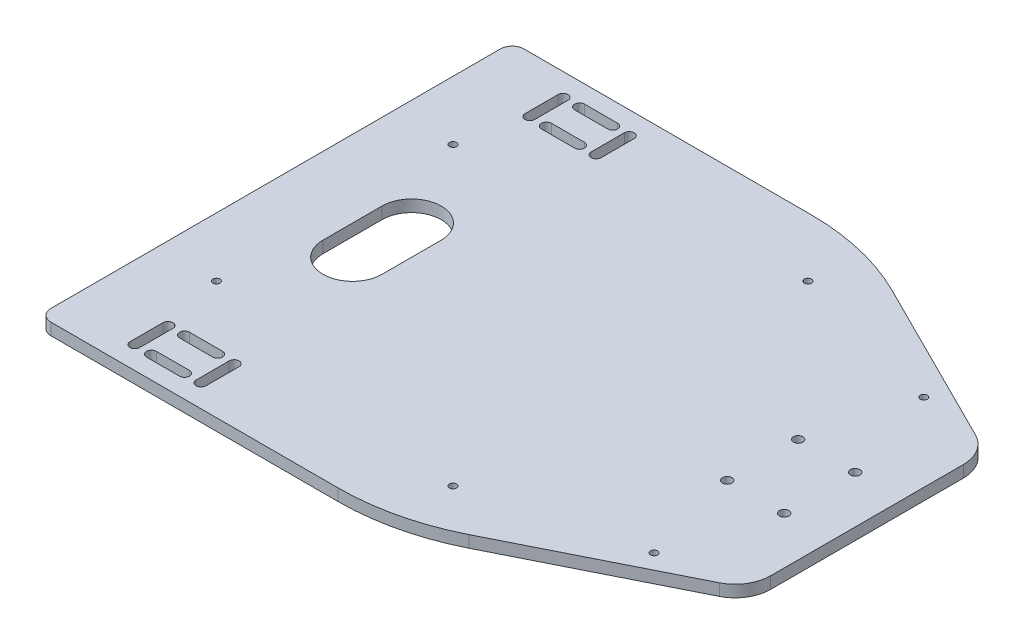
SolidWorks part; units mm, degrees
other "Markup1"
sketch "Sketch6" plane through (-125, 0, -100) normal (0, 1, 0) x (1, 0, 0)
other "Markup2"
sketch "Sketch13" plane through (-125, 0, -100) normal (0, 1, 0) x (1, 0, 0)
other "DetailItem1"
other "DetailItem2"
other "DetailItem4"
other "DetailItem5"
other "DetailItem6"
other "DetailItem7"
material "Acrylic (Medium-high impact)"
ref_plane "Front Plane" through (0, 0, 0) normal (0, 0, 1) x (1, 0, 0)
ref_plane "Top Plane" through (0, 0, 0) normal (0, 1, 0) x (1, 0, 0)
ref_plane "Right Plane" through (0, 0, 0) normal (1, 0, 0) x (0, 0, -1)
sketch "Sketch1" plane through (0, 0, 0) normal (0, 1, 0) x (1, 0, 0)
  line L1 (-120, 100) -> (1.3932, 100)
  line L2 (-125, 95) -> (-125, -95)
  line L3 (-120, -100) -> (1.3932, -100)
  line L4 (125, 40.7295) -> (125, -40.7295)
  line L5 (-125, 100) -> (125, -100) construction
  line L6 (-125, -100) -> (125, 100) construction
  line L7 (46.1146, 89.4427) -> (116.7082, 54.1459)
  line L8 (46.1146, -89.4427) -> (116.7082, -54.1459)
  arc A0 (1.3932, -100) -> (46.1146, -89.4427) centre (1.3932, 0) ccw
  arc A1 (1.3932, 100) -> (46.1146, 89.4427) centre (1.3932, 0) cw
  arc A2 (116.7082, -54.1459) -> (125, -40.7295) centre (110, -40.7295) ccw
  arc A3 (116.7082, 54.1459) -> (125, 40.7295) centre (110, 40.7295) cw
  arc A4 (-125, -95) -> (-120, -100) centre (-120, -95) ccw
  arc A5 (-120, 100) -> (-125, 95) centre (-120, 95) ccw
  point P0 (0, 0)
  point P12 (25, -100)
  point P15 (25, 100)
  point P18 (125, -50)
  point P21 (125, 50)
  dimension "D7" = 100
  dimension "D8" = 15
  dimension "D9" = 5
  dimension "D1" = 200
  dimension "D2" = 250
  dimension "D3" = 100
  dimension "D4" = 100
  dimension "D5" = 50
  dimension "D6" = 100
extrude "Boss-Extrude2" add sketch "Sketch1" against normal blind 5
sketch "Sketch7" plane through (0, 0, 0) normal (0, 1, 0) x (1, 0, 0)
  line L0 (-100, 50.0036) -> (-100, -50.0036) construction
  line L1 (-125, 95) -> (-125, -95) construction
  circle A0 centre (-100, 50.0036) radius 1.5
  circle A1 centre (-100, -49.9964) radius 1.5
  circle A2 centre (25, 75.0036) radius 1.5
  circle A4 centre (25, -74.9964) radius 1.5
  point P9 (-100, 0)
  dimension "D1" = 100
  dimension "D5" = 125
  dimension "D4" = 25
  dimension "D2" = 125
  dimension "D3" = 25
  dimension "D6" = 25
extrude "Cut-Extrude1" cut sketch "Sketch7" against normal blind 5
sketch "Sketch8" plane through (0, 0, 0) normal (0, 1, 0) x (1, 0, 0)
  line L0 (1.3932, 100) -> (-120, 100) construction
  line L1 (-100, 100) -> (-60, 100) construction
  line L2 (-100, 100) -> (-100, 70) construction
  line L3 (-100, 70) -> (-60, 70) construction
  line L4 (-60, 100) -> (-60, 70) construction
  line L5 (-125, 95) -> (-125, -95) construction
  line L8 (-96.1, 90.5) -> (-96.1, 76.5)
  line L10 (-91.9, 90.5) -> (-91.9, 76.5)
  line L11 (-68.1, 90.5) -> (-68.1, 76.5)
  line L13 (-63.9, 90.5) -> (-63.9, 76.5)
  line L14 (-87, 88.4) -> (-73, 88.4)
  line L16 (-87, 92.6) -> (-73, 92.6)
  line L18 (-87, 74.4) -> (-73, 74.4)
  line L20 (-87, 78.6) -> (-73, 78.6)
  line L21 (-125, 0) -> (47.5239, 0) construction
  line L23 (-87, -78.6) -> (-73, -78.6)
  line L24 (-87, -74.4) -> (-73, -74.4)
  line L25 (-87, -92.6) -> (-73, -92.6)
  line L26 (-87, -88.4) -> (-73, -88.4)
  line L27 (-63.9, -90.5) -> (-63.9, -76.5)
  line L28 (-68.1, -90.5) -> (-68.1, -76.5)
  line L29 (-91.9, -90.5) -> (-91.9, -76.5)
  line L30 (-96.1, -90.5) -> (-96.1, -76.5)
  arc A0 (-91.9, 90.5) -> (-96.1, 90.5) centre (-94, 90.5) ccw
  arc A1 (-96.1, 76.5) -> (-91.9, 76.5) centre (-94, 76.5) ccw
  arc A2 (-63.9, 90.5) -> (-68.1, 90.5) centre (-66, 90.5) ccw
  arc A3 (-68.1, 76.5) -> (-63.9, 76.5) centre (-66, 76.5) ccw
  arc A4 (-87, 92.6) -> (-87, 88.4) centre (-87, 90.5) ccw
  arc A5 (-73, 88.4) -> (-73, 92.6) centre (-73, 90.5) ccw
  arc A6 (-87, 78.6) -> (-87, 74.4) centre (-87, 76.5) ccw
  arc A7 (-73, 74.4) -> (-73, 78.6) centre (-73, 76.5) ccw
  arc A8 (-73, -74.4) -> (-73, -78.6) centre (-73, -76.5) cw
  arc A9 (-87, -78.6) -> (-87, -74.4) centre (-87, -76.5) cw
  arc A10 (-73, -88.4) -> (-73, -92.6) centre (-73, -90.5) cw
  arc A11 (-87, -92.6) -> (-87, -88.4) centre (-87, -90.5) cw
  arc A12 (-68.1, -76.5) -> (-63.9, -76.5) centre (-66, -76.5) cw
  arc A13 (-63.9, -90.5) -> (-68.1, -90.5) centre (-66, -90.5) cw
  arc A14 (-96.1, -76.5) -> (-91.9, -76.5) centre (-94, -76.5) cw
  arc A15 (-91.9, -90.5) -> (-96.1, -90.5) centre (-94, -90.5) cw
  dimension "D3" = 14
  dimension "D4" = 14
  dimension "D5" = 14
  dimension "D6" = 14
  dimension "D9" = 2.1
  dimension "D10" = 2.1
  dimension "D11" = 2.1
  dimension "D12" = 2.1
  dimension "D15" = 2.1
  dimension "D1" = 40
  dimension "D2" = 30
  dimension "D7" = 9.5
  dimension "D8" = 6.5
  dimension "D13" = 6
  dimension "D14" = 6
  dimension "D16" = 7
  dimension "D17" = 7
  dimension "D18" = 25
extrude "Cut-Extrude2" cut sketch "Sketch8" against normal blind 5
sketch "Sketch9" plane through (0, 0, 0) normal (0, 1, 0) x (1, 0, 0)
  line L1 (9.2183, 57.5) -> (49.2183, 57.5)
  line L2 (9.2183, 57.5) -> (9.2183, -57.5)
  line L3 (9.2183, -57.5) -> (49.2183, -57.5)
  line L4 (49.2183, 57.5) -> (49.2183, -57.5)
  line L5 (9.2183, 57.5) -> (49.2183, -57.5) construction
  line L6 (9.2183, -57.5) -> (49.2183, 57.5) construction
  point P0 (29.2183, 0)
sketch "Sketch11" plane through (0, 0, 0) normal (0, 1, 0) x (1, 0, 0)
  line L1 (-56.1717, 1.0988) -> (-11.1717, 1.0988)
  line L2 (-56.1717, 1.0988) -> (-56.1717, -43.9012)
  line L3 (-56.1717, -43.9012) -> (-11.1717, -43.9012)
  line L4 (-11.1717, 1.0988) -> (-11.1717, -43.9012)
  line L5 (-56.1717, 1.0988) -> (-11.1717, -43.9012) construction
  line L6 (-56.1717, -43.9012) -> (-11.1717, 1.0988) construction
  point P0 (-33.6717, -21.4012)
  dimension "D1" = 45
  dimension "D2" = 45
sketch "Sketch12" plane through (0, 0, 0) normal (0, 1, 0) x (1, 0, 0)
  line L1 (-57.1344, 43.8603) -> (-12.1344, 43.8603)
  line L2 (-57.1344, 43.8603) -> (-57.1344, 23.8603)
  line L3 (-57.1344, 23.8603) -> (-12.1344, 23.8603)
  line L4 (-12.1344, 43.8603) -> (-12.1344, 23.8603)
  line L5 (-57.1344, 43.8603) -> (-12.1344, 23.8603) construction
  line L6 (-57.1344, 23.8603) -> (-12.1344, 43.8603) construction
  point P0 (-34.6344, 33.8603)
  dimension "D1" = 45
  dimension "D2" = 20
sketch "Sketch14" plane through (0, 0, 0) normal (0, 1, 0) x (1, 0, 0)
  circle A0 centre (92, -56.9938) radius 1.5
  circle A1 centre (92, 56.9996) radius 1.5
extrude "Cut-Extrude3" cut sketch "Sketch14" against normal through all
sketch "Sketch16" plane through (0, 0, 0) normal (0, 1, 0) x (1, 0, 0)
  line L0 (125, -40.7295) -> (125, 40.7295) construction
  line L2 (125, 0) -> (65.3464, 0) construction
  circle A0 centre (80.9, 15) radius 2
  circle A2 centre (105, 15) radius 2
  circle A4 centre (105, -15) radius 2
  circle A5 centre (80.9, -15) radius 2
  dimension "D1" = 4
  dimension "D2" = 24.1
  dimension "D3" = 4
  dimension "D4" = 20
  dimension "D6" = 15
extrude "Cut-Extrude4" cut sketch "Sketch16" against normal through all contours A0 | A2 | A5 | A4
sketch "Sketch17" plane through (0, 0, 0) normal (0, 1, 0) x (1, 0, 0)
  line L2 (-67.5, 12.5) -> (-67.5, -12.5)
  line L4 (-92.5, 12.5) -> (-92.5, -12.5)
  line L5 (-67.5, 12.5) -> (-92.5, -12.5) construction
  line L6 (-67.5, -12.5) -> (-92.5, 12.5) construction
  arc A0 (-67.5, 12.5) -> (-92.5, 12.5) centre (-80, 12.5) ccw
  arc A1 (-92.5, -12.5) -> (-67.5, -12.5) centre (-80, -12.5) ccw
  point P0 (-80, 0)
  point P6 (-80, 25)
  point P8 (-80, -25)
  dimension "D1" = 80
  dimension "D2" = 25
  dimension "D3" = 25
  dimension "D4" = 50
extrude "Cut-Extrude5" cut sketch "Sketch17" against normal blind 5
sketch "Sketch18" plane through (0, 0, 0) normal (0, 1, 0) x (1, 0, 0)
  line L1 (9.9067, 55) -> (49.9067, 55)
  line L2 (9.9067, 55) -> (9.9067, -55)
  line L3 (9.9067, -55) -> (49.9067, -55)
  line L4 (49.9067, 55) -> (49.9067, -55)
  line L5 (9.9067, 55) -> (49.9067, -55) construction
  line L6 (9.9067, -55) -> (49.9067, 55) construction
  point P0 (29.9067, 0)
  dimension "D1" = 110
  dimension "D2" = 40
